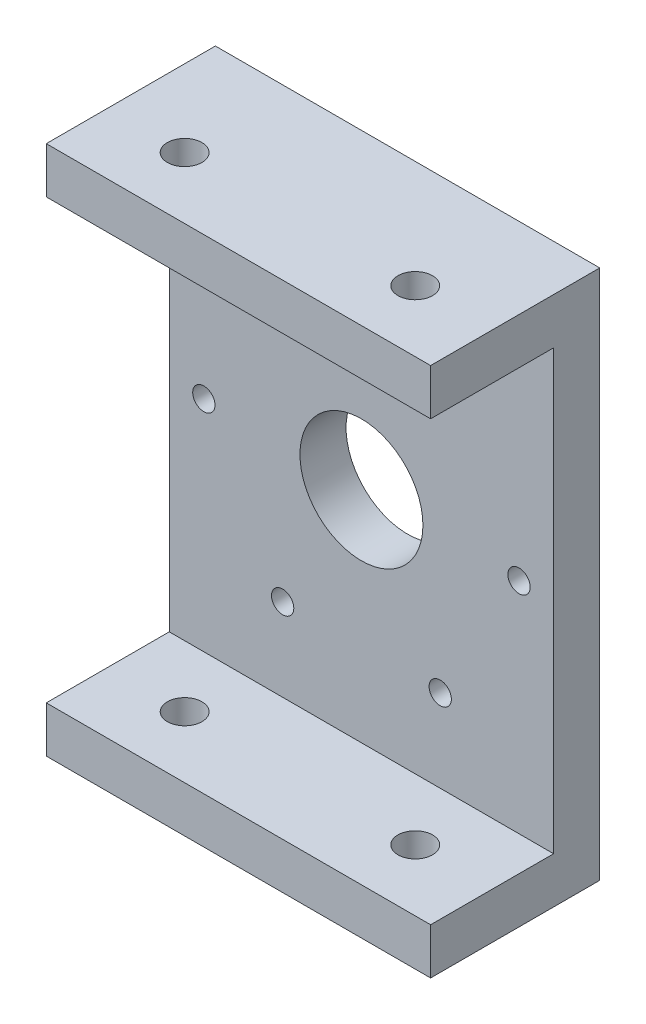
SolidWorks part; units mm, degrees
material "Aleación 6061"
ref_plane "Alzado" through (0, 0, 0) normal (0, 0, 1) x (1, 0, 0)
ref_plane "Planta" through (0, 0, 0) normal (0, 1, 0) x (1, 0, 0)
ref_plane "Vista lateral" through (0, 0, 0) normal (1, 0, 0) x (0, 0, -1)
sketch "Sk_Repisa" plane through (0, 0, 0) normal (0, 0, 1) x (1, 0, 0)
  line L1 (-25, -34.5) -> (25, -34.5)
  line L2 (-25, -34.5) -> (-25, 34.5)
  line L3 (-25, 34.5) -> (25, 34.5)
  line L4 (25, -34.5) -> (25, 34.5)
  line L5 (-25, -34.5) -> (25, 34.5) construction
  line L6 (-25, 34.5) -> (25, -34.5) construction
  point P0 (0, 0)
  dimension "D1" = 50
  dimension "D2" = 69
extrude "Repisa" add sketch "Sk_Repisa" along normal blind 6 from offset 520
sketch "Sk_Centro_motor" plane through (0, 0, 0) normal (0, 0, 1) x (1, 0, 0)
  circle A0 centre (0, 0) radius 8
  dimension "D1" = 16
extrude "Centro_motor" cut sketch "Sk_Centro_motor" along normal blind 6 from offset 520
sketch "Sk_Pasantes_M2-5_estator_J6" plane through (0, 0, 0) normal (0, 0, 1) x (1, 0, 0)
  circle A0 centre (20.5, 0) radius 1.45
  circle A1 centre (10.25, 17.7535) radius 1.45
  circle A2 centre (-10.25, 17.7535) radius 1.45
  circle A3 centre (-20.5, 0) radius 1.45
  circle A4 centre (-10.25, -17.7535) radius 1.45
  circle A5 centre (10.25, -17.7535) radius 1.45
  dimension "D1" = 2.9
  dimension "D3" = 2.9
  dimension "D6" = 2.9
  dimension "D9" = 2.9
  dimension "D11" = 2.9
  dimension "D14" = 2.9
  dimension "D2" = 20.5
  dimension "D4" = 10.25
  dimension "D5" = 17.7535
  dimension "D7" = 10.25
  dimension "D8" = 17.7535
  dimension "D10" = 20.5
  dimension "D12" = 10.25
  dimension "D13" = 17.7535
  dimension "D15" = 10.25
  dimension "D16" = 17.7535
extrude "Pasantes_M2-5_estator_J6" cut sketch "Sk_Pasantes_M2-5_estator_J6" along normal blind 6 from offset 520
sketch "Sk_Pestanas" plane through (0, 0, 0) normal (0, 0, 1) x (1, 0, 0)
  line L1 (-25, 28.5) -> (25, 28.5)
  line L2 (-25, 28.5) -> (-25, 34.5)
  line L3 (-25, 34.5) -> (25, 34.5)
  line L4 (25, 28.5) -> (25, 34.5)
  line L5 (-25, 28.5) -> (25, 34.5) construction
  line L6 (-25, 34.5) -> (25, 28.5) construction
  line L7 (-25, -34.5) -> (25, -34.5)
  line L8 (-25, -34.5) -> (-25, -28.5)
  line L9 (-25, -28.5) -> (25, -28.5)
  line L10 (25, -34.5) -> (25, -28.5)
  line L11 (-25, -34.5) -> (25, -28.5) construction
  line L12 (-25, -28.5) -> (25, -34.5) construction
  point P0 (0, 31.5)
  point P6 (0, -31.5)
  dimension "D1" = 50
  dimension "D2" = 6
  dimension "D3" = 31.5
  dimension "D4" = 50
  dimension "D5" = 6
  dimension "D6" = 31.5
extrude "Pestanas" add sketch "Sk_Pestanas" along normal blind 16 from offset 526
sketch "Sk_Pasantes_M4_pestanas" plane through (0, 0, 0) normal (0, 1, 0) x (1, 0, 0)
  circle A0 centre (-15, -534) radius 2.25
  circle A1 centre (15, -534) radius 2.25
  dimension "D1" = 4.5
  dimension "D4" = 4.5
  dimension "D2" = 15
  dimension "D3" = 534
  dimension "D5" = 15
  dimension "D6" = 534
extrude "Pasantes_M4_pestanas" cut sketch "Sk_Pasantes_M4_pestanas" along normal blind 69 from offset 34.5
